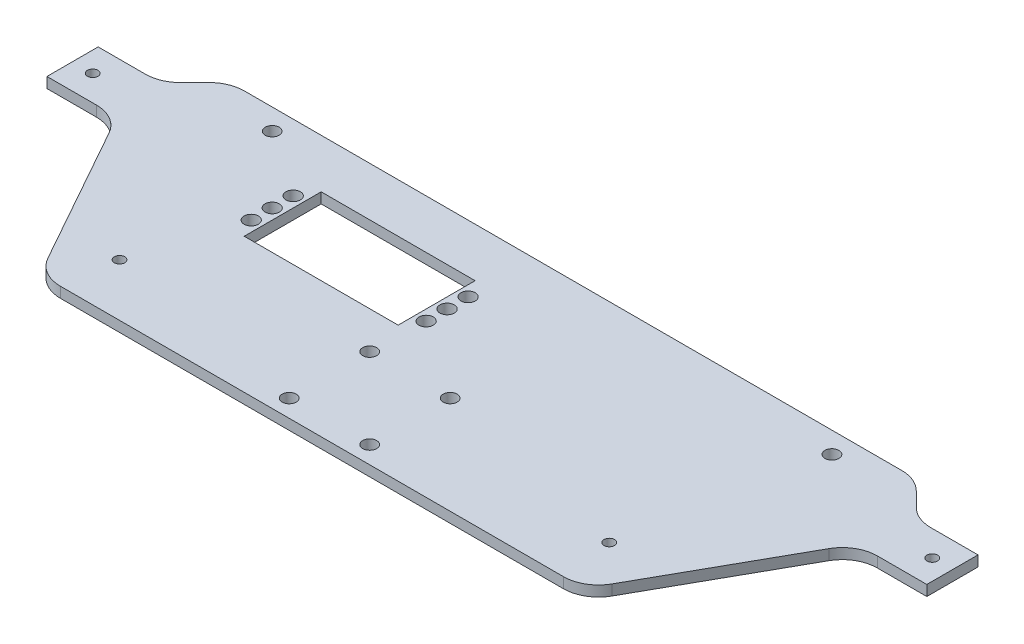
SolidWorks part; units mm, degrees
ref_plane "Alzado" through (0, 0, 0) normal (0, 0, 1) x (1, 0, 0)
ref_plane "Planta" through (0, 0, 0) normal (0, 1, 0) x (1, 0, 0)
ref_plane "Vista lateral" through (0, 0, 0) normal (1, 0, 0) x (0, 0, -1)
sketch "Croquis1" plane through (0, 0, 0) normal (0, 1, 0) x (1, 0, 0)
  line L0 (-27.8825, 0) -> (38.5584, 0) construction
  line L1 (-88.1, 42.3182) -> (88.1, 42.3182)
  line L2 (-77.75, -42.3182) -> (77.75, -42.3182)
  line L3 (-88.1, 42.3182) -> (-108.1, 22.3182)
  line L4 (-108.1, 22.3182) -> (-127.75, 22.3182)
  line L5 (0, 0) -> (0, 27.7067) construction
  line L6 (-127.75, 22.3182) -> (-127.75, 7.6818)
  line L7 (-127.75, 7.6818) -> (-105.75, 7.6818)
  line L8 (-105.75, 7.6818) -> (-77.75, -42.3182)
  line L9 (88.1, 42.3182) -> (108.1, 22.3182)
  line L10 (108.1, 22.3182) -> (127.75, 22.3182)
  line L11 (127.75, 22.3182) -> (127.75, 7.6818)
  line L12 (127.75, 7.6818) -> (105.75, 7.6818)
  line L13 (105.75, 7.6818) -> (77.75, -42.3182)
  dimension "D1" = 255.5
  dimension "D2" = 84.6363
  dimension "D3" = 19.65
  dimension "D4" = 22
  dimension "D5" = 22
  dimension "D6" = 50
  dimension "D7" = 50
  dimension "D8" = 50
  dimension "D9" = 20
  dimension "D10" = 20
  dimension "D11" = 19.65
extrude "Saliente-Extruir1" add sketch "Croquis1" along normal blind 3
fillet "Redondeo1" radius 10 8 edges at (88.1, 1.5, -42.3182) (-88.1, 1.5, -42.3182) (-77.75, 1.5, 42.3182) (77.75, 1.5, 42.3182) (108.1, 1.5, -22.3182) (105.75, 1.5, -7.6818) (-105.75, 1.5, -7.6818) (-108.1, 1.5, -22.3182)
sketch "Croquis2" plane through (0, 3, 0) normal (0, 1, 0) x (1, 0, 0)
  line L0 (0, 0) -> (0, -87.7887) construction
  line L1 (-119.9961, 22.3182) -> (-119.9961, 40.4374) construction
  line L2 (-112.2421, 22.3182) -> (-127.75, 22.3182) construction
  line L3 (-127.75, 15) -> (-123.2915, 15) construction
  line L4 (-127.75, 22.3182) -> (-127.75, 7.6818) construction
  line L5 (119.9961, 22.3182) -> (119.9961, 29.1715) construction
  line L6 (127.75, 22.3182) -> (112.2421, 22.3182) construction
  line L7 (115.6048, 15) -> (126.3231, 15) construction
  line L8 (83.9579, 42.3182) -> (-83.9579, 42.3182) construction
  line L9 (-57, 17.3182) -> (-15, 17.3182)
  line L10 (-71.8888, -42.3182) -> (71.8888, -42.3182) construction
  line L11 (-15, 17.3182) -> (-15, -2.6818)
  line L12 (-15, -2.6818) -> (-57, -2.6818)
  line L13 (-57, -2.6818) -> (-57, 17.3182)
  line L14 (-57, 7.3182) -> (-2.6959, 7.3182) construction
  line L15 (-36, 17.3182) -> (-36, 33.9331) construction
  line L16 (-11, 7.3182) -> (-11, 14.1752) construction
  line L17 (-61, 7.3182) -> (-61, 4.4352) construction
  circle A0 centre (70, -27.3182) radius 1.5
  circle A1 centre (-70, -27.3182) radius 1.5
  circle A2 centre (-119.9961, 15) radius 1.5
  circle A3 centre (119.9961, 15) radius 1.5
  circle A6 centre (-11.5, -14.3182) radius 2
  circle A7 centre (11.5, -14.3182) radius 2
  circle A8 centre (-11.5, -37.3182) radius 2
  circle A9 centre (11.5, -37.3182) radius 2
  circle A10 centre (-61, 7.3182) radius 2.05
  circle A11 centre (-11, 7.3182) radius 2.05
  circle A12 centre (-61, 13.3182) radius 2.05
  circle A13 centre (-61, 1.3182) radius 2.05
  circle A14 centre (-11, 13.3182) radius 2.05
  circle A15 centre (-11, 1.3182) radius 2.05
  dimension "D1" = 3
  dimension "D2" = 3
  dimension "D10" = 3
  dimension "D11" = 3
  dimension "D17" = 4
  dimension "D18" = 4
  dimension "D19" = 4
  dimension "D20" = 4
  dimension "D25" = 50
  dimension "D27" = 4.1
  dimension "D28" = 4.1
  dimension "D29" = 4.1
  dimension "D30" = 4.1
  dimension "D31" = 4.1
  dimension "D32" = 4.1
  dimension "D9" = 140
  dimension "D12" = 15
  dimension "D13" = 23
  dimension "D14" = 23
  dimension "D15" = 5
  dimension "D16" = 23
  dimension "D21" = 42
  dimension "D22" = 20
  dimension "D23" = 30
  dimension "D24" = 25
  dimension "D26" = 50
  dimension "D33" = 6
  dimension "D34" = 6
  dimension "D35" = 6
  dimension "D36" = 6
extrude "Cortar-Extruir1" cut sketch "Croquis2" against normal through all
sketch "Croquis3" plane through (0, 3, 0) normal (0, 1, 0) x (1, 0, 0)
  line L0 (-123.75, 22.3182) -> (-123.75, 7.6818)
  line L1 (-112.2421, 22.3182) -> (-127.75, 22.3182) construction
  line L2 (-127.75, 7.6818) -> (-111.6112, 7.6818) construction
  line L3 (-123.75, 7.6818) -> (-127.75, 7.6818)
  line L4 (-127.75, 7.6818) -> (-127.75, 22.3182)
  line L5 (-127.75, 22.3182) -> (-123.75, 22.3182)
  line L6 (127.75, 7.6818) -> (127.75, 22.3182)
  line L7 (127.75, 22.3182) -> (123.75, 22.3182)
  line L8 (127.75, 22.3182) -> (112.2421, 22.3182) construction
  line L9 (123.75, 22.3182) -> (123.75, 7.6818)
  line L10 (111.6112, 7.6818) -> (127.75, 7.6818) construction
  line L11 (123.75, 7.6818) -> (127.75, 7.6818)
  dimension "D1" = 4
  dimension "D2" = 4
extrude "Cortar-Extruir2" cut sketch "Croquis3" against normal through all
sketch "Croquis4" plane through (0, 3, 0) normal (0, 1, 0) x (1, 0, 0)
  line L0 (-36, 17.3182) -> (-36, -16.9775) construction
  line L1 (-15, 17.3182) -> (-57, 17.3182) construction
  line L2 (-57, 7.3182) -> (-47.1795, 7.3182) construction
  line L3 (-57, 17.3182) -> (-57, -2.6818) construction
  line L4 (-58, 18.3182) -> (-58, -3.6818)
  line L5 (-58, -3.6818) -> (-14, -3.6818)
  line L6 (-14, -3.6818) -> (-14, 18.3182)
  line L7 (-58, 18.3182) -> (-14, 18.3182)
  line L8 (-15, -2.6818) -> (-15, 17.3182) construction
  line L9 (-57, -2.6818) -> (-15, -2.6818) construction
  dimension "D1" = 1
  dimension "D2" = 1
  dimension "D3" = 1
  dimension "D4" = 1
extrude "Cortar-Extruir3" cut sketch "Croquis4" against normal through all
sketch "Croquis5" plane through (0, 3, 0) normal (0, 1, 0) x (1, 0, 0)
  line L0 (-63.75, 42.3182) -> (-38.75, 32.3182)
  line L1 (83.9579, 42.3182) -> (-83.9579, 42.3182) construction
  line L2 (-38.75, 32.3182) -> (38.75, 32.3182)
  line L3 (38.75, 32.3182) -> (63.75, 42.3182)
  line L4 (63.75, 42.3182) -> (-63.75, 42.3182)
  line L5 (-123.75, 7.6818) -> (-123.75, 22.3182) construction
  line L6 (123.75, 22.3182) -> (123.75, 7.6818) construction
  line L7 (0, 42.3182) -> (0, 71.9714) construction
  dimension "D1" = 60
  dimension "D2" = 60
  dimension "D3" = 10
  dimension "D4" = 25
extrude "Cortar-Extruir4" cut sketch "Croquis5" against normal through all
fillet "Redondeo2" radius 20 4 edges at (63.75, 1.5, -42.3182) (-63.75, 1.5, -42.3182) (-38.75, 1.5, -32.3182) (38.75, 1.5, -32.3182)
sketch "Croquis6" plane through (0, 3, 0) normal (0, 1, 0) x (1, 0, 0)
  line L0 (-34.8984, 32.3182) -> (-98.1, 32.3182)
  line L1 (-91.0289, 39.3892) -> (-105.1711, 25.2471) construction
  line L2 (-98.1, 50.6044) -> (105.4279, 50.6044)
  line L3 (105.4279, 50.6044) -> (105.4279, 32.3182)
  line L4 (105.4279, 32.3182) -> (-34.8984, 32.3182)
  line L5 (-98.1, 50.6044) -> (-98.1, 32.3182)
extrude "Cortar-Extruir5" cut sketch "Croquis6" against normal blind 10
fillet "Redondeo3" radius 10 2 edges at (98.1, 1.5, -32.3182) (-98.1, 1.5, -32.3182)
sketch "Croquis7" plane through (-123.75, 0, 0) normal (-1, 0, 0) x (0, 0, 1)
  line L4 (-7.6818, 3) -> (-22.3182, 3)
  line L5 (-22.3182, 3) -> (-22.3182, 0)
  line L6 (-22.3182, 0) -> (-7.6818, 0)
  line L7 (-7.6818, 0) -> (-7.6818, 3)
  line L8 (-7.6818, 3) -> (-22.3182, 3)
  line L9 (-22.3182, 3) -> (-22.3182, 0)
  line L10 (-22.3182, 0) -> (-7.6818, 0)
  line L11 (-7.6818, 0) -> (-7.6818, 3)
  dimension "D1" = 0
extrude "Saliente-Extruir2" add sketch "Croquis7" along normal blind 2
sketch "Croquis8" plane through (123.75, 0, 0) normal (1, 0, 0) x (0, 0, -1)
  line L4 (22.3182, 3) -> (7.6818, 3)
  line L5 (7.6818, 3) -> (7.6818, 0)
  line L6 (7.6818, 0) -> (22.3182, 0)
  line L7 (22.3182, 0) -> (22.3182, 3)
  line L8 (22.3182, 3) -> (7.6818, 3)
  line L9 (7.6818, 3) -> (7.6818, 0)
  line L10 (7.6818, 0) -> (22.3182, 0)
  line L11 (22.3182, 0) -> (22.3182, 3)
  dimension "D1" = 0
extrude "Saliente-Extruir3" add sketch "Croquis8" along normal blind 2
sketch "Croquis10" plane through (0, 3, 0) normal (0, 1, 0) x (1, 0, 0)
  line L0 (0, 32.3182) -> (0, 50.0251) construction
  line L1 (-93.9579, 32.3182) -> (93.9579, 32.3182) construction
  circle A0 centre (-80, 26.3182) radius 2
  circle A1 centre (80, 26.3182) radius 2
  dimension "D1" = 160
  dimension "D2" = 4
  dimension "D3" = 4
  dimension "D4" = 6
extrude "Cortar-Extruir7" cut sketch "Croquis10" against normal through all
